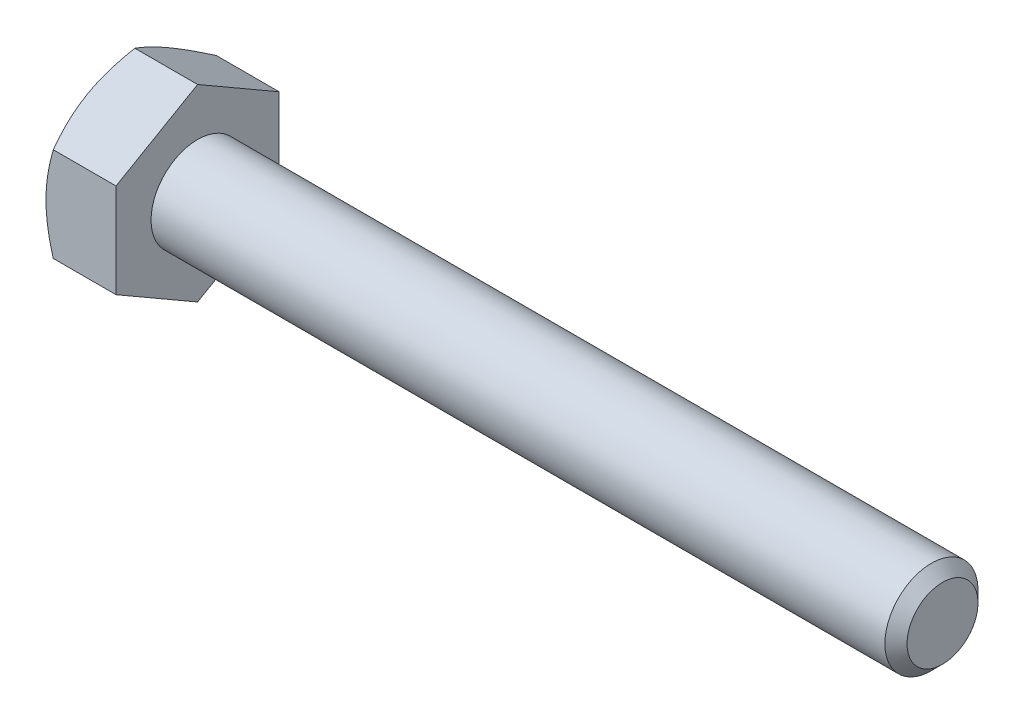
SolidWorks part; units mm, degrees
ref_plane "Plane1" through (0, 0, 0) normal (0, 0, 1) x (1, 0, 0)
ref_plane "Plane2" through (0, 0, 0) normal (0, 1, 0) x (1, 0, 0)
ref_plane "Plane3" through (0, 0, 0) normal (1, 0, 0) x (0, 0, -1)
sketch "Sketch1" plane through (0, 0, 0) normal (1, 0, 0) x (0, 0, -1)
  line L0 (5.5626, 3.2116) -> (5.5626, -3.2116)
  line L1 (-5.5626, 3.2116) -> (-5.5626, -3.2116)
  line L2 (5.5626, -3.2116) -> (0, -6.4231)
  line L3 (0, -6.4231) -> (-5.5626, -3.2116)
  line L4 (5.5626, 3.2116) -> (0, 6.4231)
  line L5 (0, 6.4231) -> (-5.5626, 3.2116)
  dimension "Width_flats" = 11.1252
  dimension "D2" = 120
  dimension "D3" = 5.5626
  dimension "D4" = 5.5626
  dimension "D5" = 5.5626
extrude "BaseHead" add sketch "Sketch1" along normal blind 4.7752
sketch "BodySke" plane through (0, 0, 0) normal (0, 0, 1) x (1, 0, 0)
  line L0 (0, 3.2116) -> (0, -3.2116) construction
  line L1 (0, 0) -> (55.5752, 0)
  line L2 (0, 0) -> (0, 3.175)
  line L3 (0, 3.175) -> (54.8195, 3.175)
  line L4 (55.5752, 0) -> (55.5752, 2.4193)
  line L5 (4.7752, 6.4231) -> (4.7752, 3.2116) construction
  line L6 (55.5752, 2.4193) -> (54.8195, 3.175)
  line L7 (0, 0) -> (96.52, 0) construction
  line L8 (55.5752, -2.4193) -> (54.8195, -3.175) construction
  line L9 (0, -3.175) -> (54.8195, -3.175) construction
  line L10 (6.0452, 15.24) -> (6.0452, -2.54) construction
  line L11 (36.5252, 15.24) -> (36.5252, -2.54) construction
  line L12 (4.7752, 3.2116) -> (4.7752, -3.2116) construction
  dimension "Length" = 50.8
  dimension "Body_ch_ang" = 45
  dimension "Diameter" = 6.35
  dimension "Minor_dia" = 4.8387
  dimension "Advance" = 1.27
  dimension "Thread_nom" = 19.05
revolve "BaseBody" add sketch "BodySke" angle 360 about L7
cosmetic thread "ThreadCosmetic" [suppressed] parameters "Thread_length"=19.05, "Thread_minor"=4.8387
sketch "Sketch3" plane through (0, 0, 0) normal (0, 0, 1) x (1, 0, 0)
  line L0 (0, 5.5626) -> (4.163, 12.7731)
  line L1 (0, 6.4231) -> (0, 3.2116) construction
  line L2 (4.163, 12.7731) -> (4.163, 19.1231)
  line L3 (4.163, 19.1231) -> (-12.7, 19.1231)
  line L4 (-12.7, 19.1231) -> (-12.7, 5.5626)
  line L5 (-12.7, 5.5626) -> (0, 5.5626)
  line L6 (0, 0) -> (99.06, 0) construction
  line L7 (4.7752, 6.4231) -> (0, 6.4231) construction
  dimension "D1" = 5.5626
  dimension "D2" = 6.35
  dimension "D3" = 12.7
  dimension "D4" = 6.35
  dimension "Head_ch_ang" = 30
revolve "HeadChamfer" cut sketch "Sketch3" angle 360 about L6
fillet "HeadFillet" [suppressed] radius 0.762
sketch "ThdSchSke" plane through (0, 0, 0) normal (0, 0, 1) x (1, 0, 0)
  line L0 (36.5252, -2.4193) -> (35.9961, -3.175)
  line L1 (36.5252, -2.4193) -> (37.0543, -3.175)
  line L2 (37.0543, -3.175) -> (37.0543, -3.9688)
  line L3 (-3.175, 0) -> (5.1513, 0) construction
  line L5 (37.0543, -3.9688) -> (35.9961, -3.9688)
  line L6 (35.9961, -3.9688) -> (35.9961, -3.175)
  dimension "Thread_minor" = 4.8387
  dimension "Diameter" = 6.35
  dimension "Start" = 36.5252
  dimension "SideAngle" = 55
  dimension "VeeAngle" = 70
  dimension "Overcut" = 7.9375
revolve "ThreadSchematic" [suppressed] cut sketch "ThdSchSke" angle 360 about L3
pattern_linear "ThdSchPat" [suppressed]
equation "\"D3@Sketch1\" = \"Width_flats@Sketch1\" / 2"
equation "\"D4@Sketch1\" = \"D3@Sketch1\""
equation "\"D5@Sketch1\" = \"D4@Sketch1\""
equation "\"Thread_minor@ThreadCosmetic\" = \"Minor_dia@BodySke\""
equation "\"D1@Sketch3\" = \"Width_flats@Sketch1\" / 2"
equation "\"Thread_length@ThreadCosmetic\" = ((sgn( (\"Length@BodySke\" - \"Advance@BodySke\" ) - \"Thread_nom@BodySke\" )-1)*( (\"Length@BodySke\" - \"Advance@BodySke\" ) - \"Thread_nom@BodySke\" ))/-2+ \"Thread_nom@BodySke\""
equation "\"Thread_minor@ThdSchSke\" = \"Minor_dia@BodySke\""
equation "\"Diameter@ThdSchSke\" = \"Diameter@BodySke\""
equation "\"Overcut@ThdSchSke\" = \"Diameter@BodySke\" * 1.25"
equation "\"Start@ThdSchSke\" = \"Head_ht@BaseHead\" + \"Length@BodySke\" - \"Thread_length@ThreadCosmetic\"  '---Non-countersunk---"
equation "\"Num_threads@ThdSchPat\" = int( \"Thread_length@ThreadCosmetic\" / \"Advance@BodySke\" + 0.999 )  + 1"
equation "\"Advance@ThdSchPat\" = \"Thread_length@ThreadCosmetic\" /  (\"Num_threads@ThdSchPat\" - 1) 'relax it"
equation "\"Num_threads@ThdSchPat\" = \"Num_threads@ThdSchPat\" - sgn( \"Num_threads@ThdSchPat\" - 1) '---chamfered tips only---"
